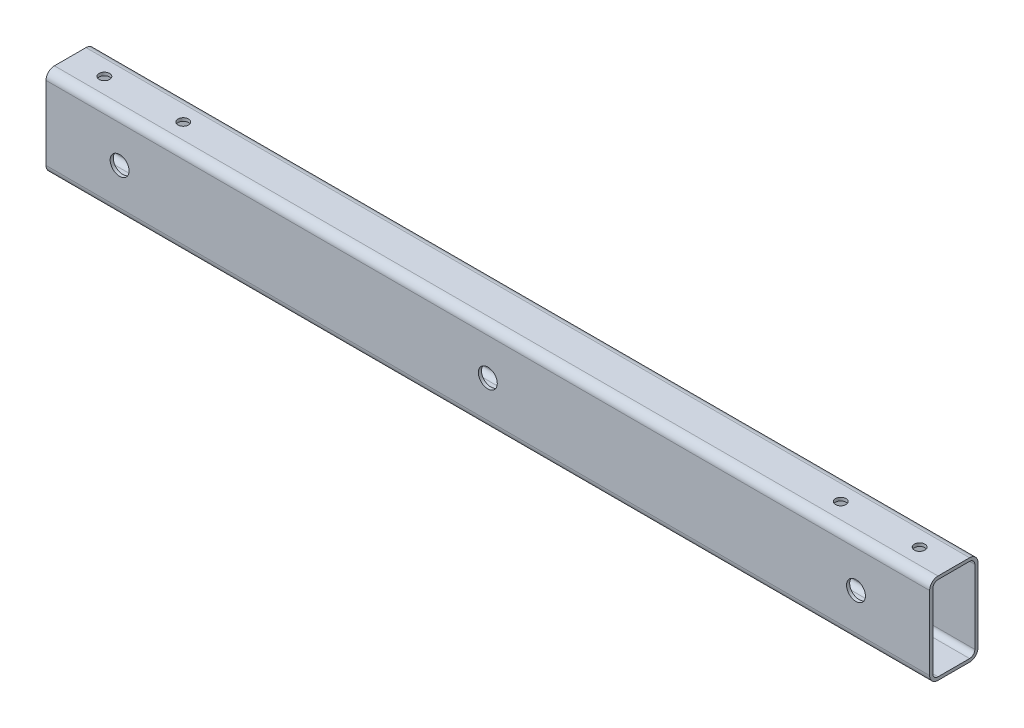
SolidWorks part; units mm, degrees
ref_plane "Front Plane" through (0, 0, 0) normal (0, 0, 1) x (1, 0, 0)
ref_plane "Top Plane" through (0, 0, 0) normal (0, 1, 0) x (1, 0, 0)
ref_plane "Right Plane" through (0, 0, 0) normal (1, 0, 0) x (0, 0, -1)
sketch "Sketch1" plane through (0, 0, 0) normal (1, 0, 0) x (0, 0, -1)
  line L1 (-15, -40) -> (15, -40)
  line L2 (-20, -35) -> (-20, 35)
  line L3 (-15, 40) -> (15, 40)
  line L4 (20, -35) -> (20, 35)
  line L5 (-20, -40) -> (20, 40) construction
  line L6 (-20, 40) -> (20, -40) construction
  arc A0 (-20, -35) -> (-15, -40) centre (-15, -35) ccw
  arc A1 (15, -40) -> (20, -35) centre (15, -35) ccw
  arc A2 (20, 35) -> (15, 40) centre (15, 35) ccw
  arc A3 (-15, 40) -> (-20, 35) centre (-15, 35) ccw
  point P0 (0, 0)
  dimension "D3" = 5
  dimension "D1" = 40
  dimension "D2" = 80
extrude "Extrude-Thin1" add sketch "Sketch1" along normal blind 420 and the other way blind 420 thin
sketch "Sketch2" plane through (0, 0, 0) normal (0, 0, 1) x (1, 0, 0)
  line L0 (0, -25.3) -> (0, 25.3) construction
  circle A0 centre (0, 0) radius 9
  circle A1 centre (-350, 0) radius 9
  circle A2 centre (350, 0) radius 9
  point P9 (0, 0)
  point P10 (0, 0)
  dimension "D1" = 18
  dimension "D2" = 350
extrude "Cut-Extrude1" cut sketch "Sketch2" against normal through all both and the other way through all
sketch "Sketch3" plane through (0, 0, 0) normal (0, 1, 0) x (1, 0, 0)
  line L1 (0, -25.3) -> (0, 25.3) construction
  circle A0 centre (-387.5, 0) radius 5
  circle A1 centre (-312.5, 0) radius 5
  circle A2 centre (312.5, 0) radius 5
  circle A3 centre (387.5, 0) radius 5
  point P4 (0, 0)
  point P5 (0, 0)
  dimension "D1" = 10
  dimension "D2" = 75
  dimension "D3" = 312.5
extrude "Cut-Extrude2" cut sketch "Sketch3" against normal through all both and the other way through all
